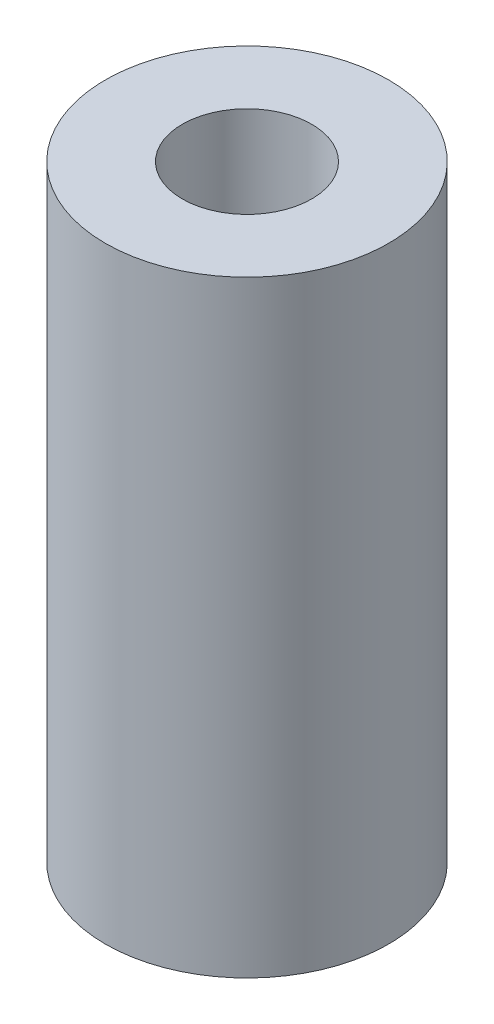
SolidWorks part; units mm, degrees
material "ABS"
ref_plane "Plano frontal" through (0, 0, 0) normal (0, 0, 1) x (1, 0, 0)
ref_plane "Plano superior" through (0, 0, 0) normal (0, 1, 0) x (1, 0, 0)
ref_plane "Plano direito" through (0, 0, 0) normal (1, 0, 0) x (0, 0, -1)
sketch "Esboço1" plane through (0, 0, 0) normal (0, 1, 0) x (1, 0, 0)
  circle A0 centre (0, 0) radius 1.6
  circle A1 centre (0, 0) radius 3.5
  dimension "D1" = 3.2
  dimension "D2" = 7
extrude "Ressalto-extrusão1" add sketch "Esboço1" along normal mid plane 15
